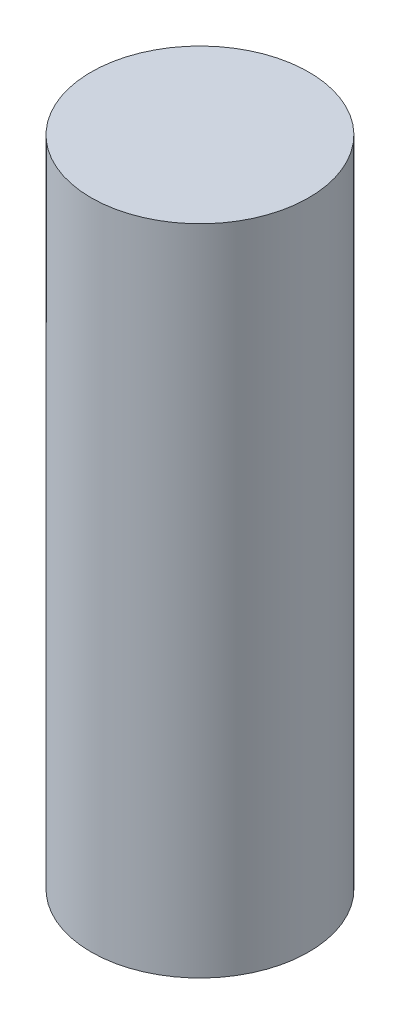
SolidWorks part; units mm, degrees
ref_plane "前视基准面" through (0, 0, 0) normal (0, 0, 1) x (1, 0, 0)
ref_plane "上视基准面" through (0, 0, 0) normal (0, 1, 0) x (1, 0, 0)
ref_plane "右视基准面" through (0, 0, 0) normal (1, 0, 0) x (0, 0, -1)
sketch "草图1" plane through (0, 0, 0) normal (0, 1, 0) x (1, 0, 0)
  circle A0 centre (0, 0) radius 12.5
extrude "凸台-拉伸1" add sketch "草图1" along normal blind 75
